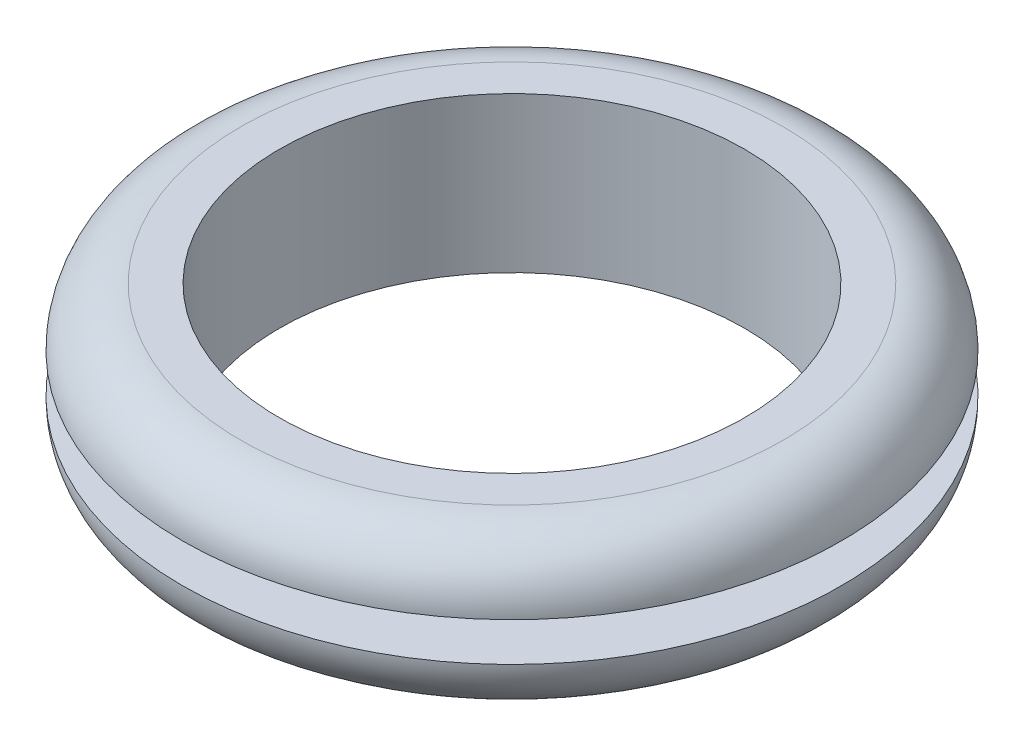
SolidWorks part; units mm, degrees
material "Rubber"
ref_plane "Front" through (0, 0, 0) normal (0, 0, 1) x (1, 0, 0)
ref_plane "Top" through (0, 0, 0) normal (0, 1, 0) x (1, 0, 0)
ref_plane "Right" through (0, 0, 0) normal (1, 0, 0) x (0, 0, -1)
sketch "Sketch1" plane through (0, 0, 0) normal (1, 0, 0) x (0, 0, -1)
  line L0 (0, -6.35) -> (0, 6.35) construction
  line L1 (0, 1.5875) -> (0, -1.5875) construction
  line L2 (-26.9875, 6.35) -> (26.9875, 6.35) construction
  line L3 (-19.05, 1.5875) -> (19.05, 1.5875) construction
  line L4 (-22.225, 0) -> (22.225, 0) construction
  point P12 (-19.05, 1.5875)
  point P13 (19.05, 1.5875)
  point P14 (-22.225, 0)
  point P15 (22.225, 0)
  point P16 (-26.9875, 6.35)
  point P17 (0, -6.35)
  point P18 (26.9875, 6.35)
  point P19 (0, 6.35)
  point P20 (0, 1.5875)
  point P21 (0, -1.5875)
  dimension "Overall Height E" = 12.7
  dimension "Material Thickness B" = 3.175
  dimension "Flange Diameter D" = 53.975
  dimension "ID C" = 38.1
  dimension "For ID A" = 44.45
sketch "Sketch2" plane through (0, 0, 0) normal (1, 0, 0) x (0, 0, -1)
  line L0 (-19.05, -6.35) -> (-19.05, 6.35)
  line L1 (-19.05, 6.35) -> (-22.225, 6.35)
  line L2 (-22.225, 1.5875) -> (-22.225, -1.5875)
  line L3 (-22.225, 1.5875) -> (-26.9875, 1.5875)
  line L4 (-22.225, -1.5875) -> (-26.9875, -1.5875)
  line L5 (-19.05, -6.35) -> (-22.225, -6.35)
  arc A0 (-26.9875, 1.5875) -> (-22.225, 6.35) centre (-22.225, 1.5875) cw
  arc A1 (-26.9875, -1.5875) -> (-22.225, -6.35) centre (-22.225, -1.5875) ccw
  point P4 (-26.9875, 1.5875)
revolve "Revolve1" add sketch "Sketch2" angle 360 about L0
ref_plane "Plane1" through (0, 6.35, 0) normal (0, -1, 0) x (0, 0, -1)
sketch "Sketch3" plane through (0, 6.35, 0) normal (0, -1, 0) x (0, 0, -1)
  line L0 (0, -26.9875) -> (0, 26.9875) construction
  line L1 (-26.9875, 0) -> (26.9875, 0) construction
  line L2 (0, 19.05) -> (0, -19.05) construction
  line L3 (-19.05, 0) -> (19.05, 0) construction
  line L4 (0, 22.225) -> (0, -22.225) construction
  line L5 (-22.225, 0) -> (22.225, 0) construction
  point P11 (0, 26.9875)
  point P12 (0, 19.05)
  point P13 (0, -19.05)
  point P14 (0, -26.9875)
  point P19 (0, -22.225)
  point P20 (0, 22.225)
